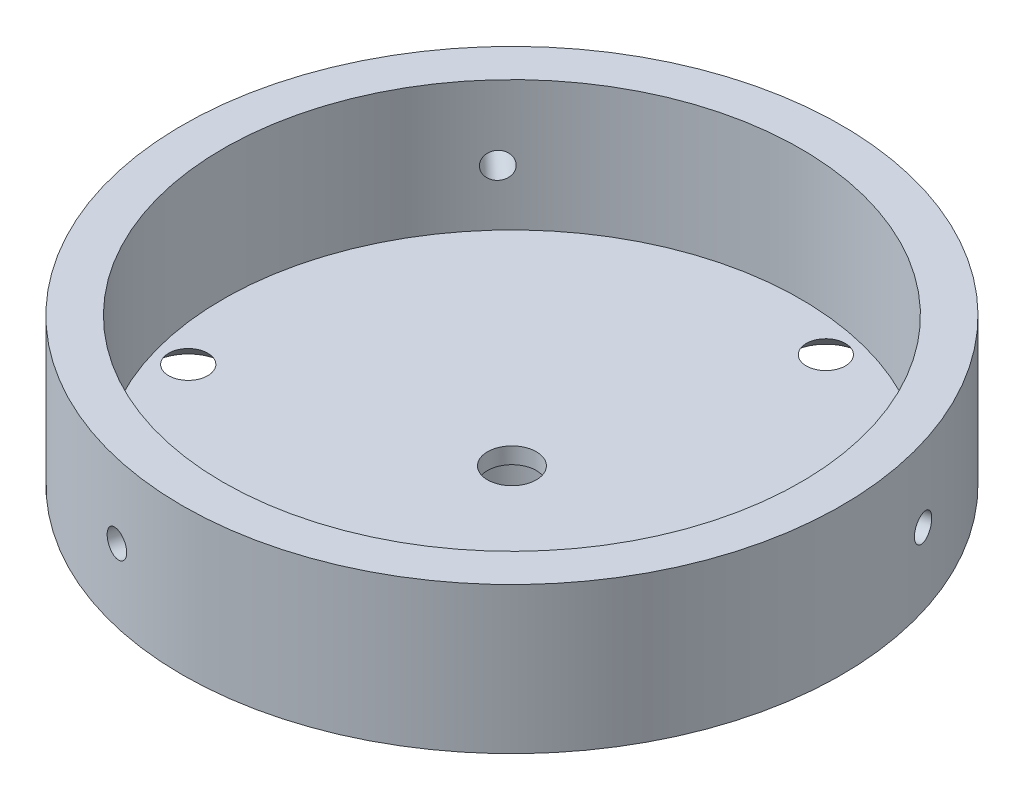
SolidWorks part; units mm, degrees
ref_plane "Front Plane" through (0, 0, 0) normal (0, 0, 1) x (1, 0, 0)
ref_plane "Top Plane" through (0, 0, 0) normal (0, 1, 0) x (1, 0, 0)
ref_plane "Right Plane" through (0, 0, 0) normal (1, 0, 0) x (0, 0, -1)
sketch "Sketch1" plane through (0, 0, 0) normal (0, 1, 0) x (1, 0, 0)
  circle A0 centre (0, 0) radius 20.25
  dimension "D1" = 40.5
extrude "Boss-Extrude1" add sketch "Sketch1" along normal blind 9
sketch "Sketch2" plane through (0, 9, 0) normal (0, 1, 0) x (1, 0, 0)
  circle A0 centre (0, 0) radius 17.75
  dimension "D1" = 35.5
extrude "Cut-Extrude1" cut sketch "Sketch2" against normal blind 8
hole_wizard "CSK SLOT for M2 Countersunk Flat Head Screw1" positions "Sketch3" profile "Sketch4" size "M2" standard "ISO" slot yes
sketch "Sketch3" plane through (0, 0, 0) normal (0, -1, 0) x (-1, 0, 0)
  line L0 (-11.6097, -11.0097) -> (0, 0)
  point P0 (-11.6097, -11.0097)
  dimension "D1" = 16
sketch "Sketch4" plane through (11.6097, 0, 11.0097) normal (1, 0, 0) x (0, 0, -1)
  line L0 (0, 0) -> (0, 6.521)
  line L1 (0, 6.521) -> (1.2, 5.8)
  line L2 (1.2, 5.8) -> (1.2, 1)
  line L3 (1.2, 1) -> (2.2, 0)
  line L5 (2.2, 0) -> (0, 0)
  line L6 (-1.2, 1) -> (-2.2, 0) construction
  line L10 (0, 6.521) -> (-1.2, 5.8) construction
  line L11 (0, -6.35) -> (0, 107.95) construction
  dimension "Hole Dia." = 2.4
  dimension "Hole Depth" = 5.8
  dimension "Near C'Sink Dia." = 4.4
  dimension "Near C'Sink Angle" = 90
  dimension "Drill Angle" = 118
pattern_circular "CirPattern1" count 3 over 360 about axis through (0, 0, 0) along (0, 1, 0) of "CSK SLOT for M2 Countersunk Flat Head Screw1"
sketch "Sketch5" plane through (0, 0, 0) normal (0, -1, 0) x (1, 0, 0)
  circle A0 centre (0, 0) radius 1.5
  dimension "D1" = 3
extrude "Cut-Extrude2" cut sketch "Sketch5" against normal blind 8
hole_wizard "M2 Tapped Hole1" positions "3DSketch1" profile "Sketch6" tap size "M2" standard "ISO"
sketch3d "3DSketch1"
  point P0 (-4.5608, 4.4458, 19.7297)
sketch "Sketch6" plane through (-4.5608, 4.4458, 19.7297) normal (0, 1, 0) x (0.9743, 0, 0.2252)
  line L0 (0, 0) -> (0, 4.9807)
  line L1 (0, 4.9807) -> (0.8, 4.5)
  line L2 (0.8, 4.5) -> (0.8, 0)
  line L5 (0.8, 0) -> (0, 0)
  line L10 (0, 4.9807) -> (-0.8, 4.5) construction
  line L11 (0, -6.35) -> (0, 107.95) construction
  dimension "Tap Drill Dia." = 1.6
  dimension "Tap Drill Depth" = 4.5
  dimension "Drill Angle" = 118
pattern_circular "CirPattern2" count 3 over 360 about axis through (0, 9, 0) along (0, -1, 0) of "M2 Tapped Hole1"
sketch "Sketch7" plane through (0, 0, 0) normal (0, -1, 0) x (1, 0, 0)
  circle A0 centre (0, 0) radius 4
  dimension "D1" = 8
extrude "Boss-Extrude3" add sketch "Sketch7" along normal blind 4
sketch "Sketch8" plane through (0, -4, 0) normal (0, -1, 0) x (1, 0, 0)
  circle A0 centre (0, 0) radius 3.265
  dimension "D1" = 6.53
extrude "Cut-Extrude3" cut sketch "Sketch8" against normal blind 4
